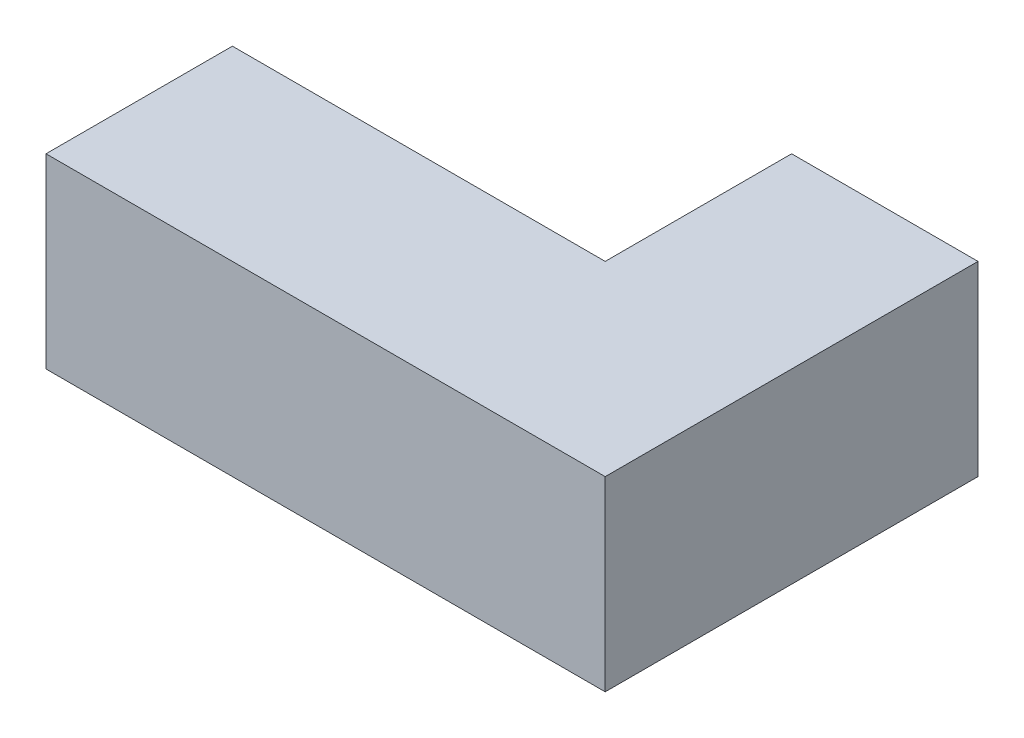
SolidWorks part; units mm, degrees
material "Oak"
ref_plane "Front Plane" through (0, 0, 0) normal (0, 0, 1) x (1, 0, 0)
ref_plane "Top Plane" through (0, 0, 0) normal (0, 1, 0) x (1, 0, 0)
ref_plane "Right Plane" through (0, 0, 0) normal (1, 0, 0) x (0, 0, -1)
sketch "Sketch1" plane through (0, 0, 0) normal (0, 1, 0) x (1, 0, 0)
  line L0 (0, 0) -> (90, 0)
  line L1 (90, 0) -> (90, 60)
  line L2 (90, 60) -> (60, 60)
  line L3 (60, 60) -> (60, 30)
  line L4 (0, 0) -> (0, 30)
  line L5 (0, 30) -> (60, 30)
  dimension "D1" = 30
  dimension "D2" = 60
  dimension "D3" = 90
extrude "Boss-Extrude1" add sketch "Sketch1" along normal blind 30
